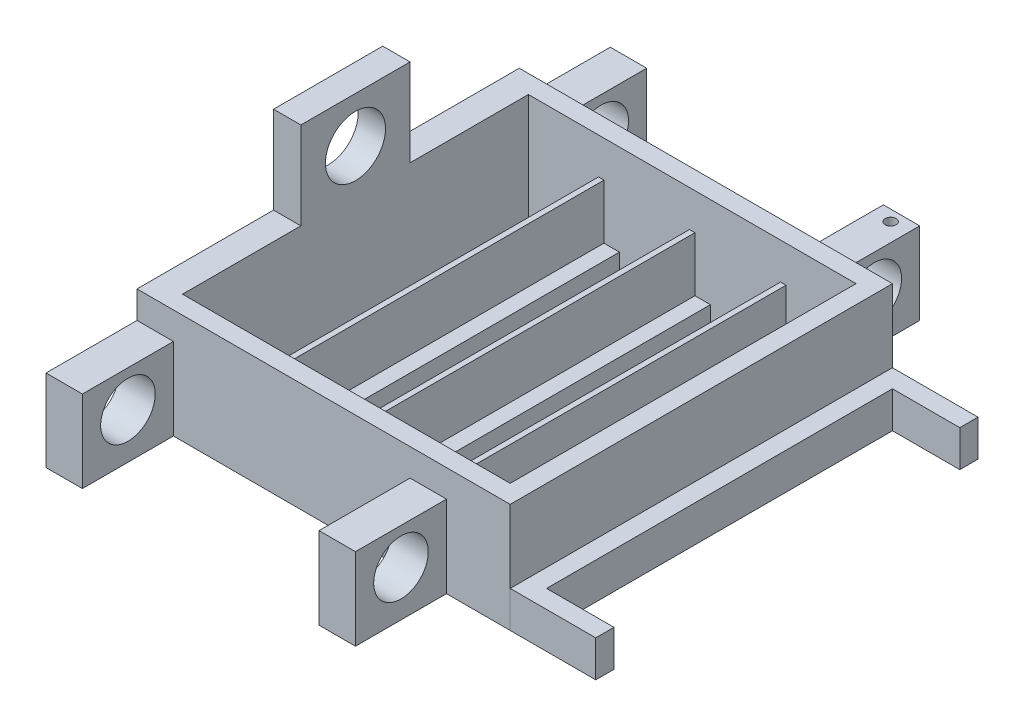
SolidWorks part; units mm, degrees
ref_plane "前视基准面" through (0, 0, 0) normal (0, 0, 1) x (1, 0, 0)
ref_plane "上视基准面" through (0, 0, 0) normal (0, 1, 0) x (1, 0, 0)
ref_plane "右视基准面" through (0, 0, 0) normal (1, 0, 0) x (0, 0, -1)
sketch "草图5" plane through (0, 0, 0) normal (0, 0, 1) x (1, 0, 0)
  line L0 (0, 0) -> (-105, 0)
  line L1 (0, 0) -> (100, 0)
  line L2 (100, 0) -> (100, 60)
  line L3 (-105, 0) -> (-105, 60)
  line L4 (-105, 60) -> (100, 60)
extrude "拉伸2" add sketch "草图5" along normal mid plane 210
sketch "草图7" plane through (0, 0, 0) normal (0, 1, 0) x (1, 0, 0)
  line L0 (0, 0) -> (189.7847, 0) construction
  line L1 (147, 95) -> (110, 95)
  line L2 (147, 105) -> (147, 95)
  line L3 (100, -105) -> (100, 105) construction
  line L4 (100, 105) -> (147, 105)
  line L7 (100, -105) -> (147, -105)
  line L8 (147, -105) -> (147, -95)
  line L9 (110, -95) -> (110, 95)
  line L10 (100, -105) -> (100, 105)
  line L11 (147, -95) -> (110, -95)
  point P10 (100, 0)
  point P11 (110, 0)
  dimension "D2" = 10
  dimension "D1" = 10
  dimension "D3" = 47
extrude "拉伸4" add sketch "草图7" along normal blind 30 separate body
shell "抽壳1" thickness 10
ref_plane "基准面1" through (0, 38, 0) normal (0, 1, 0) x (-1, 0, 0)
sketch "草图9" plane through (-105, 0, 0) normal (-1, 0, 0) x (0, 0, 1)
  line L0 (105, 60) -> (105, 0) construction
  line L1 (105, 10) -> (155, 10)
  line L2 (105, 10) -> (105, 55)
  line L3 (105, 55) -> (155, 55)
  line L4 (155, 10) -> (155, 55)
  line L5 (105, 0) -> (-105, 0) construction
  circle A0 centre (130, 35) radius 15
  dimension "D1" = 10
  dimension "D2" = 35
  dimension "D3" = 25
extrude "拉伸6" add sketch "草图9" against normal blind 20 separate body
pattern_linear "阵列(线性)2" count 2 spacing 150 along (1, 0, 0) of bodies 152
mirror "镜向1" about plane through (0, 0, 0) normal (0, 0, 1) of bodies 152 153
sketch "草图10" plane through (100, 0, 0) normal (1, 0, 0) x (0, 0, -1)
  line L0 (0, 0) -> (0, 60) construction
  line L1 (-105, 60) -> (105, 60) construction
  line L2 (30, 60) -> (-30, 60)
  line L3 (-30, 60) -> (-30, 110)
  line L4 (-30, 110) -> (30, 110)
  line L5 (30, 60) -> (30, 110)
  point P9 (0, 110)
extrude "拉伸7" [suppressed] add sketch "草图10" against normal blind 10
sketch "草图11" [suppressed] plane through (100, 0, 0) normal (1, 0, 0) x (0, 0, -1)
  line L0 (0, 110) -> (0, 60) construction
  line L1 (30, 110) -> (-30, 110) construction
  line L2 (-30, 85) -> (30, 85) construction
  line L3 (-30, 110) -> (-30, 60) construction
  line L4 (30, 60) -> (30, 110) construction
  circle A0 centre (0, 85) radius 10
extrude "拉伸8" [suppressed] cut sketch "草图11" against normal blind 10
sketch "草图12" plane through (-105, 0, 0) normal (-1, 0, 0) x (0, 0, 1)
  line L0 (0, 0) -> (0, 95.0984) construction
  line L1 (105, 60) -> (-105, 60) construction
  line L2 (-30, 60) -> (30, 60)
  line L3 (-30, 60) -> (-30, 118)
  line L4 (-30, 118) -> (30, 118)
  line L5 (30, 60) -> (30, 118)
  line L6 (105, 0) -> (-105, 0) construction
  circle A0 centre (0, 93) radius 16.5
  dimension "D4" = 93
  dimension "D5" = 33
  dimension "D1" = 30
  dimension "D2" = 60
  dimension "D3" = 58
extrude "拉伸9" add sketch "草图12" against normal blind 10 separate body
sketch "草图14" plane through (-95, 0, 0) normal (1, 0, 0) x (0, 0, -1)
  line L0 (-30, 60) -> (-95, 60)
  line L1 (95, 0) -> (-95, 0)
  line L2 (95, 0) -> (95, 60)
  line L3 (95, 60) -> (30, 60)
  line L4 (-95, 0) -> (-95, 60)
  line L6 (30, 60) -> (30, 118)
  line L7 (30, 118) -> (-30, 118)
  line L8 (-30, 60) -> (-30, 118)
  circle A0 centre (0, 93) radius 16.5
  dimension "D1" = 33
extrude "拉伸11" add sketch "草图14" along normal blind 5
sketch "草图8" plane through (0, 0, 0) normal (0, 1, 0) x (1, 0, 0)
  line L0 (90, -95) -> (90, 95) construction
  line L1 (60, 95) -> (40, 95)
  line L2 (90, 95) -> (-90, 95) construction
  line L3 (40, 95) -> (40, -95)
  line L4 (60, 95) -> (60, -95)
  line L5 (10, 95) -> (10, -95)
  line L6 (90, -95) -> (-90, -95) construction
  line L7 (60, -95) -> (40, -95)
  line L8 (10, 95) -> (-10, 95)
  line L9 (-10, 95) -> (-10, -95)
  line L10 (10, -95) -> (-10, -95)
  line L11 (-40, 95) -> (-40, -95)
  line L12 (-40, 95) -> (-60, 95)
  line L13 (-60, 95) -> (-60, -95)
  line L14 (-40, -95) -> (-60, -95)
  dimension "D1" = 30
  dimension "D2" = 20
extrude "拉伸5" add sketch "草图8" along normal blind 20
sketch "草图15" plane through (0, 0, 105) normal (0, 0, 1) x (1, 0, 0)
  line L0 (147, 30) -> (147, 0) construction
  line L1 (-105, 0) -> (147, 0)
  line L2 (-105, 0) -> (-105, 10)
  line L3 (-105, 10) -> (147, 10)
  line L4 (147, 0) -> (147, 10)
extrude "拉伸12" cut sketch "草图15" against normal blind 219
sketch "草图16" plane through (0, 20, 0) normal (0, 1, 0) x (1, 0, 0)
  line L0 (-50, 95) -> (-50, -95) construction
  line L1 (-40, 95) -> (-60, 95) construction
  line L2 (-60, -95) -> (-40, -95) construction
  line L3 (0, -95) -> (0, 95) construction
  line L4 (-10, -95) -> (10, -95) construction
  line L5 (90, 95) -> (-90, 95) construction
  line L6 (50, 95) -> (50, -95) construction
  line L7 (60, 95) -> (40, 95) construction
  line L8 (40, -95) -> (60, -95) construction
  line L9 (10, 95) -> (-10, 95) construction
  line L10 (-51.5, -95) -> (-48.5, -95)
  line L11 (-51.5, -95) -> (-51.5, 95)
  line L12 (-51.5, 95) -> (-48.5, 95)
  line L13 (-48.5, -95) -> (-48.5, 95)
  line L14 (-51.5, -95) -> (-48.5, 95) construction
  line L15 (-51.5, 95) -> (-48.5, -95) construction
  line L16 (-1.5, -95) -> (1.5, -95)
  line L17 (-1.5, -95) -> (-1.5, 95)
  line L18 (-1.5, 95) -> (1.5, 95)
  line L19 (1.5, -95) -> (1.5, 95)
  line L20 (-1.5, -95) -> (1.5, 95) construction
  line L21 (-1.5, 95) -> (1.5, -95) construction
  line L23 (48.5, -90.235) -> (51.5, -90.235)
  line L24 (48.5, -90.235) -> (48.5, 95)
  line L25 (48.5, 95) -> (51.5, 95)
  line L26 (51.5, -90.235) -> (51.5, 95)
  line L27 (48.5, -90.235) -> (51.5, 95) construction
  line L28 (48.5, 95) -> (51.5, -90.235) construction
  point P18 (-50, 0)
  point P23 (0, 0)
  point P31 (50, 2.3825)
extrude "拉伸13" add sketch "草图16" along normal blind 30
sketch "草图17" plane through (0, 60, 0) normal (0, 1, 0) x (1, 0, 0)
  line L0 (-105, 30) -> (-90, 30)
  line L1 (-105, 105) -> (100, 105)
  line L2 (-105, 105) -> (-105, 30)
  line L3 (-105, -105) -> (100, -105)
  line L4 (100, 105) -> (100, -105)
  line L5 (90, -95) -> (-90, -95)
  line L6 (90, -95) -> (90, 95)
  line L7 (90, 95) -> (-90, 95)
  line L8 (-90, -95) -> (-90, -30)
  line L9 (-90, -30) -> (-105, -30)
  line L10 (-105, -30) -> (-105, -105)
  line L11 (-90, 30) -> (-90, 95)
extrude "拉伸14" add sketch "草图17" along normal blind 10
sketch "草图18" plane through (0, 70, 0) normal (0, 1, 0) x (1, 0, 0)
  line L0 (-80, 85) -> (80, 85)
  line L1 (-90, 95) -> (90, 95)
  line L2 (-90, 95) -> (-90, -95)
  line L3 (-90, -95) -> (90, -95)
  line L4 (90, 95) -> (90, -95)
  line L5 (80, 85) -> (80, -85)
  line L6 (-80, -85) -> (80, -85)
  line L7 (-80, 85) -> (-80, -85)
  dimension "D1" = 10
extrude "拉伸15" [suppressed] add sketch "草图18" against normal blind 2 separate body
sketch "草图19" plane through (0, 55, 0) normal (0, 1, 0) x (1, 0, 0)
  line L0 (55, 155) -> (55, 105) construction
  line L1 (65, 155) -> (45, 155) construction
  line L2 (65, 105) -> (45, 105) construction
  circle A0 centre (55, 149) radius 3
  dimension "D1" = 6
extrude "拉伸16" cut sketch "草图19" against normal blind 10
